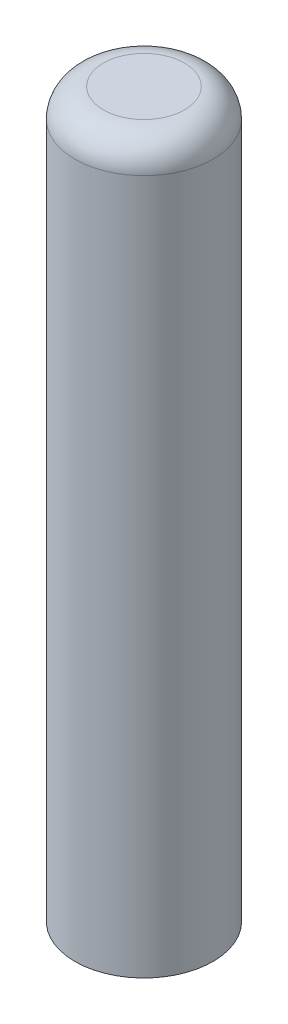
SolidWorks part; units mm, degrees
ref_plane "Front Plane" through (0, 0, 0) normal (0, 0, 1) x (1, 0, 0)
ref_plane "Top Plane" through (0, 0, 0) normal (0, 1, 0) x (1, 0, 0)
ref_plane "Right Plane" through (0, 0, 0) normal (1, 0, 0) x (0, 0, -1)
sketch "Sketch1" plane through (0, 0, 0) normal (0, 1, 0) x (1, 0, 0)
  circle A0 centre (0, 0) radius 3.15
  dimension "D1" = 6.3
extrude "Boss-Extrude1" add sketch "Sketch1" along normal blind 33
fillet "Fillet1" radius 1.3 1 edges at (0, 33, 3.15)
sketch "Sketch2" plane through (0, 0, 0) normal (0, -1, 0) x (1, 0, 0)
  circle A0 centre (0, 0) radius 1.5
  dimension "D1" = 3
extrude "Cut-Extrude1" cut sketch "Sketch2" against normal blind 12
